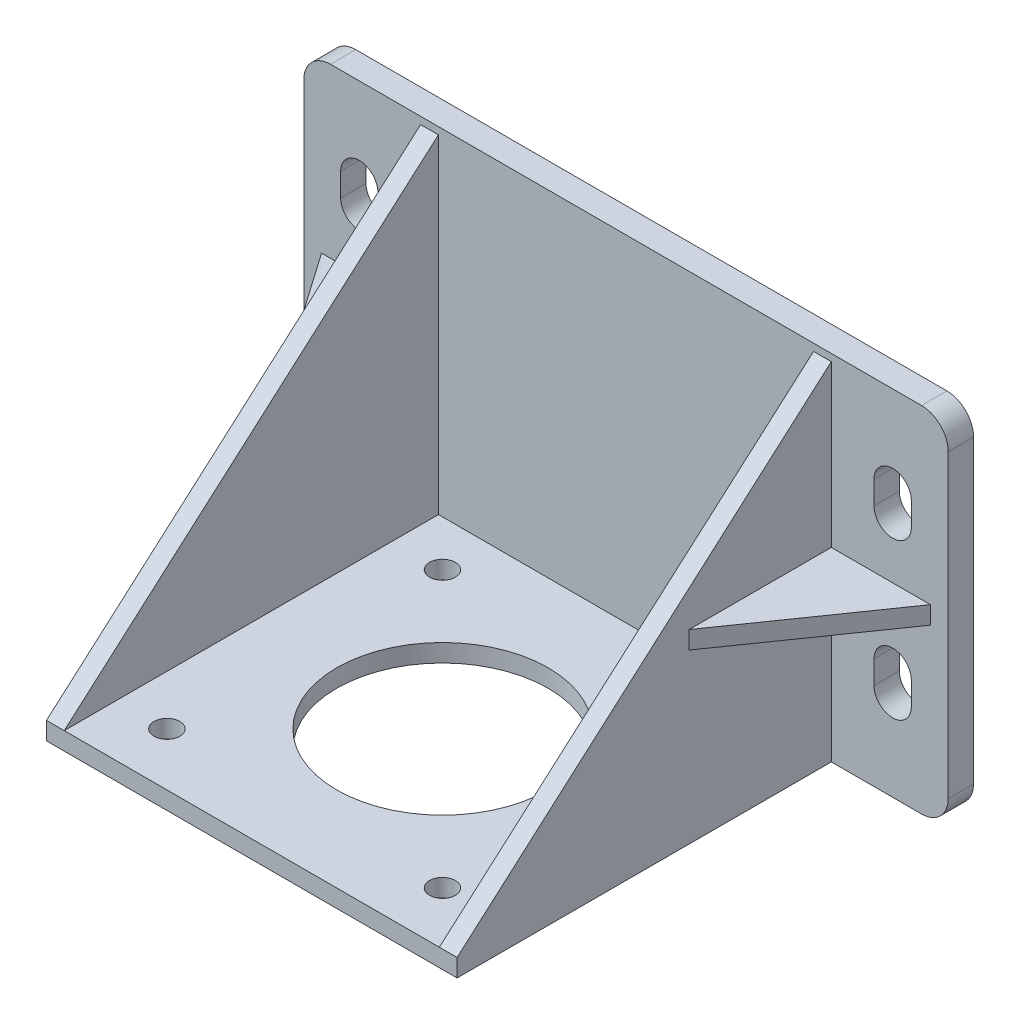
SolidWorks part; units mm, degrees
ref_plane "Front Plane" through (0, 0, 0) normal (0, 0, 1) x (1, 0, 0)
ref_plane "Top Plane" through (0, 0, 0) normal (0, 1, 0) x (1, 0, 0)
ref_plane "Right Plane" through (0, 0, 0) normal (1, 0, 0) x (0, 0, -1)
sketch "Sketch1" plane through (0, 0, 0) normal (0, 0, 1) x (1, 0, 0)
  line L0 (-30, 19.9) -> (-30, 0) construction
  line L1 (36.25, -19.9) -> (-36.25, -19.9)
  line L2 (36.25, -19.9) -> (36.25, 19.9)
  line L3 (36.25, 19.9) -> (-36.25, 19.9)
  line L4 (-36.25, -19.9) -> (-36.25, 19.9)
  line L5 (0, 19.9) -> (0, -19.9) construction
  line L6 (36.25, 0) -> (-36.25, 0) construction
  line L7 (-30, 10.05) -> (-30, 7.45) construction
  line L8 (-27.9, 10.05) -> (-27.9, 7.45)
  line L9 (-32.1, 10.05) -> (-32.1, 7.45)
  line L10 (-30, -10.05) -> (-30, -7.45) construction
  line L11 (-27.9, -10.05) -> (-27.9, -7.45)
  line L12 (-32.1, -10.05) -> (-32.1, -7.45)
  line L13 (30, 10.05) -> (30, 7.45) construction
  line L14 (27.9, 10.05) -> (27.9, 7.45)
  line L15 (32.1, 10.05) -> (32.1, 7.45)
  line L16 (30, -10.05) -> (30, -7.45) construction
  line L17 (27.9, -10.05) -> (27.9, -7.45)
  line L18 (32.1, -10.05) -> (32.1, -7.45)
  arc A0 (-27.9, 10.05) -> (-32.1, 10.05) centre (-30, 10.05) ccw
  arc A1 (-32.1, 7.45) -> (-27.9, 7.45) centre (-30, 7.45) ccw
  arc A2 (-27.9, -10.05) -> (-32.1, -10.05) centre (-30, -10.05) cw
  arc A3 (-32.1, -7.45) -> (-27.9, -7.45) centre (-30, -7.45) cw
  arc A4 (27.9, 10.05) -> (32.1, 10.05) centre (30, 10.05) cw
  arc A5 (32.1, 7.45) -> (27.9, 7.45) centre (30, 7.45) cw
  arc A6 (27.9, -10.05) -> (32.1, -10.05) centre (30, -10.05) ccw
  arc A7 (32.1, -7.45) -> (27.9, -7.45) centre (30, -7.45) ccw
  point P0 (0, 0)
  point P8 (-30, 8.75)
  point P17 (-30, -8.75)
  point P24 (30, 8.75)
  point P31 (30, -8.75)
  dimension "D3" = 6.8
  dimension "D1" = 72.5
  dimension "D2" = 39.8
  dimension "D4" = 4.2
  dimension "D5" = 60
  dimension "D6" = 17.5
extrude "Boss-Extrude1" add sketch "Sketch1" along normal blind 2.85
ref_plane "Plane1" through (0, 0, 0) normal (1, 0, 0) x (0, 0, -1)
sketch "Sketch4" plane through (0, 0, 0) normal (1, 0, 0) x (0, 0, -1)
  line L0 (-2.85, 19.1) -> (-44.95, -17.9)
  line L1 (-44.95, -17.9) -> (-44.95, -19.9)
  line L2 (-44.95, -19.9) -> (-2.85, -19.9)
  line L3 (-2.85, -19.9) -> (0, -19.9) construction
  line L4 (-2.85, -19.9) -> (-2.85, 19.1)
  line L5 (-2.85, -19.9) -> (-2.85, 19.9) construction
  line L6 (-2.85, 19.9) -> (0, 19.9) construction
  dimension "D1" = 0.8
  dimension "D2" = 42.1
  dimension "D3" = 2
extrude "Boss-Extrude2" add sketch "Sketch4" along normal mid plane 46.2
sketch "Sketch5" plane through (0, 19.9, 0) normal (0, 1, 0) x (1, 0, 0)
  line L0 (23.1, -2.85) -> (-23.1, -2.85) construction
  line L1 (-21.1, -2.85) -> (21.1, -2.85)
  line L2 (-21.1, -2.85) -> (-21.1, -44.95)
  line L3 (-21.1, -44.95) -> (21.1, -44.95)
  line L4 (21.1, -2.85) -> (21.1, -44.95)
  line L5 (23.1, -44.95) -> (-23.1, -44.95) construction
  line L6 (23.1, -2.85) -> (23.1, -44.95) construction
  line L7 (0, 0) -> (0, -2.85) construction
  dimension "D1" = 2
extrude "Cut-Extrude1" cut sketch "Sketch5" against normal offset from surface (37.8 mm away) 2 up to face at (0, -19.9, 12.6625)
sketch "Sketch6" plane through (0, -17.9, 0) normal (0, 1, 0) x (1, 0, 0)
  line L0 (36.25, 0) -> (-36.25, 0) construction
  line L1 (15.5, -39) -> (-15.5, -39) construction
  line L2 (15.5, -39) -> (15.5, -8) construction
  line L3 (15.5, -8) -> (-15.5, -8) construction
  line L4 (-15.5, -39) -> (-15.5, -8) construction
  line L5 (0, -8) -> (0, -39) construction
  line L6 (15.5, -23.5) -> (-15.5, -23.5) construction
  circle A0 centre (-15.5, -8) radius 1.45
  circle A1 centre (15.5, -8) radius 1.45
  circle A2 centre (15.5, -39) radius 1.45
  circle A3 centre (-15.5, -39) radius 1.45
  circle A4 centre (0, -23.5) radius 11.9
  point P0 (0, -23.5)
  dimension "D3" = 2.9
  dimension "D4" = 23.8
  dimension "D1" = 8
  dimension "D2" = 31
extrude "Cut-Extrude2" cut sketch "Sketch6" against normal up to next
fillet "Fillet1" radius 3 4 edges at (36.25, 19.9, 1.425) (36.25, -19.9, 1.425) (-36.25, -19.9, 1.425) (-36.25, 19.9, 1.425)
ref_plane "Plane2" through (0, 0, 0) normal (0, 1, 0) x (1, 0, 0)
sketch "Sketch7" plane through (0, 0, 0) normal (0, 1, 0) x (1, 0, 0)
  line L0 (34.25, -2.85) -> (23.1, -18.85)
  line L1 (33.25, -2.85) -> (-33.25, -2.85) construction
  line L2 (23.1, -2.85) -> (23.1, -44.95) construction
  line L3 (23.1, -18.85) -> (23.1, -2.85)
  line L4 (23.1, -2.85) -> (34.25, -2.85)
  line L5 (0, 0) -> (0, -11.6) construction
  line L6 (36.25, 0) -> (36.25, -2.85) construction
  line L7 (-23.1, -2.85) -> (-34.25, -2.85)
  line L8 (-23.1, -18.85) -> (-23.1, -2.85)
  line L9 (-34.25, -2.85) -> (-23.1, -18.85)
  circle A0 centre (0, -23.5) radius 11.9 construction
  dimension "D1" = 16
  dimension "D2" = 2
extrude "Boss-Extrude3" add sketch "Sketch7" along normal mid plane 2
